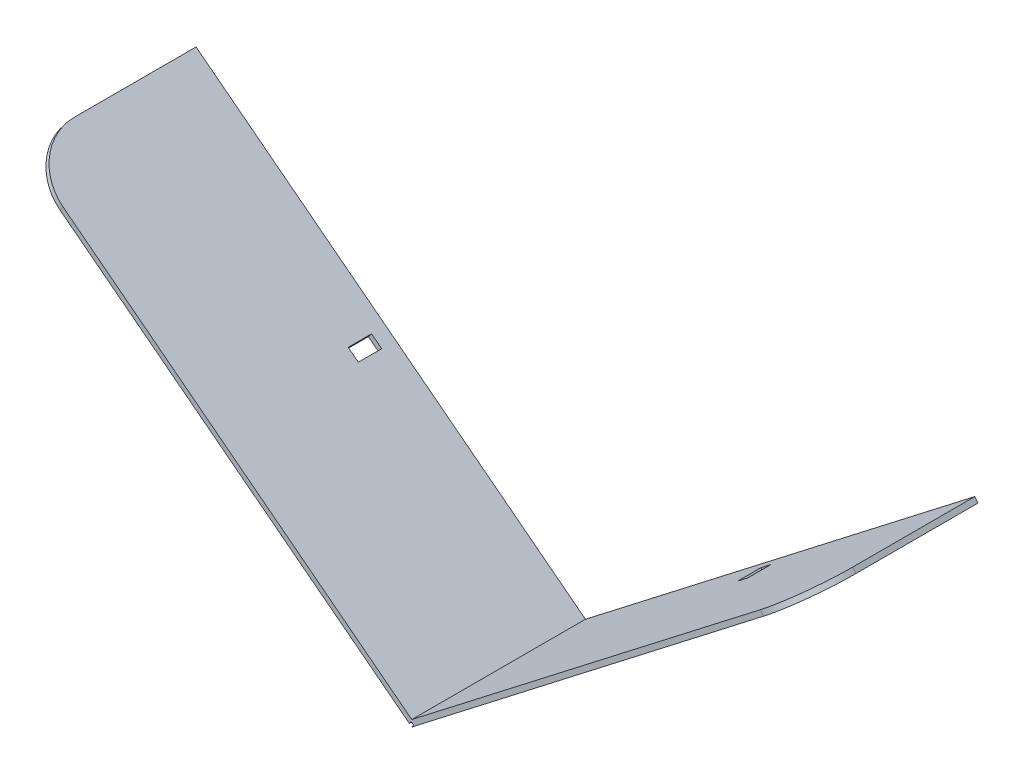
SolidWorks part; units mm, degrees
material "white foam"
ref_plane "Front Plane" through (0, 0, 0) normal (0, 0, 1) x (1, 0, 0)
ref_plane "Top Plane" through (0, 0, 0) normal (0, 1, 0) x (1, 0, 0)
ref_plane "Right Plane" through (0, 0, 0) normal (1, 0, 0) x (0, 0, -1)
sketch "Sketch1" plane through (0, 0, 0) normal (0, 0, 1) x (1, 0, 0)
  line L0 (0, 0) -> (380.0247, 293.7164)
  line L1 (0, 0) -> (-380.0247, 293.7164)
  line L2 (-380.0247, 0) -> (380.0247, 0) construction
  line L3 (0, 6.3193) -> (376.967, 297.6726)
  line L4 (0, 6.3193) -> (-376.967, 297.6726)
  line L5 (380.0247, 293.7164) -> (376.967, 297.6726)
  line L6 (-380.0247, 293.7164) -> (-376.967, 297.6726)
  point P7 (0, 0)
  dimension "D1" = 37.7
  dimension "D2" = 37.7
  dimension "D3" = 480.3
  dimension "D4" = 5
extrude "Boss-Extrude1" add sketch "Sketch1" against normal blind 240.2
sketch "Sketch2" plane through (0, 0, 0) normal (0, 1, 0) x (1, 0, 0)
  line L0 (-380.0247, 240.2) -> (-380.0247, 0) construction
  line L1 (380.0247, 240.2) -> (-380.0247, 240.2)
  line L2 (380.0247, 240.2) -> (380.0247, 168.14)
  line L3 (380.0247, 168.14) -> (-380.0247, 168.14)
  line L4 (-380.0247, 240.2) -> (-380.0247, 168.14)
  dimension "D1" = 72.06
extrude "Cut-Extrude3" cut sketch "Sketch2" along normal through all both and the other way through all contours L1 L4 L3 L2
sketch "Sketch3" plane through (3.0576, 3.9561, 0) normal (0.6115, 0.7912, 0) x (0.7912, -0.6115, 0)
  line L0 (-242.0822, 168.14) -> (-242.0822, 118.14) construction
  line L1 (-480.3, 168.14) -> (-3.8644, 168.14) construction
  line L3 (-248.2822, 131.84) -> (-235.8822, 131.84)
  line L4 (-248.2822, 131.84) -> (-248.2822, 154.44)
  line L5 (-248.2822, 154.44) -> (-235.8822, 154.44)
  line L6 (-235.8822, 131.84) -> (-235.8822, 154.44)
  line L7 (-248.2822, 131.84) -> (-235.8822, 154.44) construction
  line L8 (-248.2822, 154.44) -> (-235.8822, 131.84) construction
  point P4 (-242.0822, 143.14)
  dimension "D1" = 50
  dimension "D2" = 12.4
  dimension "D3" = 22.6
extrude "Cut-Extrude4" cut sketch "Sketch3" against normal through all both and the other way through all
mirror "Mirror1" about plane through (0, 0, 0) normal (1, 0, 0) of "Cut-Extrude4"
fillet "Fillet1" radius 50 2 edges at (-378.4958, 295.6945, 0) (378.4958, 295.6945, 0)
sketch "Sketch4" plane through (3.0576, 3.9561, 0) normal (0.6115, 0.7912, 0) x (0.7912, -0.6115, 0)
  line L0 (-96.8294, 49.07) -> (-110.8994, 35) construction
  line L1 (-86.2228, 38.4634) -> (-100.2928, 24.3934)
  line L2 (-107.436, 59.6766) -> (-121.506, 45.6066)
  line L3 (-123.0122, 123.14) -> (-201.1522, 45) construction
  line L4 (-105.3346, 105.4623) -> (-183.4746, 27.3223)
  line L5 (-140.6899, 140.8177) -> (-218.8299, 62.6777)
  line L6 (-361.1522, 123.14) -> (-283.0122, 45) construction
  line L7 (-343.4746, 140.8177) -> (-265.3346, 62.6777)
  line L8 (-378.8299, 105.4623) -> (-300.6899, 27.3223)
  line L9 (-387.335, 49.07) -> (-373.265, 35) construction
  line L10 (-376.7284, 59.6766) -> (-362.6584, 45.6066)
  line L11 (-397.9416, 38.4634) -> (-383.8716, 24.3934)
  line L12 (-3.8644, 0) -> (-430.3, 0) construction
  line L13 (-3.8644, 168.14) -> (-3.8644, 0) construction
  line L14 (-3.8644, 0) -> (-3.8644, 84.07) construction
  line L15 (-3.8644, 84.07) -> (-3.8644, 168.14) construction
  line L16 (-242.0822, 131.84) -> (-242.0822, 0) construction
  line L18 (-110.8994, 35) -> (-242.0822, 35) construction
  line L19 (-242.0822, 35) -> (-373.265, 35) construction
  line L20 (-435.3, 125.4623) -> (-435.3, 85.4623) construction
  line L21 (-420.3, 125.4623) -> (-420.3, 85.4623)
  line L22 (-450.3, 125.4623) -> (-450.3, 85.4623)
  line L23 (-480.3, 168.14) -> (-480.3, 50) construction
  line L25 (-248.2822, 131.84) -> (-235.8822, 131.84) construction
  line L26 (-3.8644, 0) -> (-430.3, 0) construction
  arc A0 (-86.2228, 38.4634) -> (-107.436, 59.6766) centre (-96.8294, 49.07) ccw
  arc A1 (-121.506, 45.6066) -> (-100.2928, 24.3934) centre (-110.8994, 35) ccw
  arc A2 (-105.3346, 105.4623) -> (-140.6899, 140.8177) centre (-123.0122, 123.14) ccw
  arc A3 (-218.8299, 62.6777) -> (-183.4746, 27.3223) centre (-201.1522, 45) ccw
  arc A4 (-343.4746, 140.8177) -> (-378.8299, 105.4623) centre (-361.1522, 123.14) ccw
  arc A5 (-300.6899, 27.3223) -> (-265.3346, 62.6777) centre (-283.0122, 45) ccw
  arc A6 (-376.7284, 59.6766) -> (-397.9416, 38.4634) centre (-387.335, 49.07) ccw
  arc A7 (-383.8716, 24.3934) -> (-362.6584, 45.6066) centre (-373.265, 35) ccw
  circle A8 centre (-242.0822, 105.4623) radius 15
  arc A9 (-420.3, 125.4623) -> (-450.3, 125.4623) centre (-435.3, 125.4623) ccw
  arc A10 (-450.3, 85.4623) -> (-420.3, 85.4623) centre (-435.3, 85.4623) ccw
  point P2 (-103.8644, 42.035)
  point P7 (-162.0822, 84.07)
  point P14 (-322.0822, 84.07)
  point P21 (-380.3, 42.035)
  point P34 (-3.8644, 84.07)
  point P40 (-3.8644, 42.035)
  point P44 (-435.3, 105.4623)
  point P59 (-242.0822, 131.84)
  dimension "D7" = 25
  dimension "D8" = 15
  dimension "D10" = 15
  dimension "D11" = 25
  dimension "D12" = 30
  dimension "D13" = 30
  dimension "D14" = 15
  dimension "D1" = 45
  dimension "D2" = 135
  dimension "D3" = 35
  dimension "D4" = 45
  dimension "D5" = 80
  dimension "D6" = 80
  dimension "D9" = 100
  dimension "D15" = 40
extrude "Cut-Extrude5" [suppressed] cut sketch "Sketch4" against normal through all both and the other way through all
mirror "Mirror2" [suppressed] about plane through (0, 0, 0) normal (1, 0, 0)
sketch "Sketch5" plane through (0, 0, 0) normal (-0.6115, -0.7912, 0) x (0.7912, -0.6115, 0)
  line L0 (0, -168.14) -> (-480.3, -168.14) construction
  line L1 (0, 0) -> (-3, 0)
  line L2 (0, 0) -> (0, -33.628)
  line L3 (0, -33.628) -> (-3, -33.628)
  line L4 (-3, 0) -> (-3, -33.628)
  line L5 (0, -33.628) -> (-3, -33.628)
  line L6 (0, -33.628) -> (0, -67.256)
  line L7 (0, -67.256) -> (-3, -67.256)
  line L8 (-3, -33.628) -> (-3, -67.256)
  line L9 (0, -67.256) -> (-3, -67.256)
  line L10 (0, -67.256) -> (0, -100.884)
  line L11 (0, -100.884) -> (-3, -100.884)
  line L12 (-3, -67.256) -> (-3, -100.884)
  line L13 (0, -100.884) -> (-3, -100.884)
  line L14 (0, -100.884) -> (0, -134.512)
  line L15 (0, -134.512) -> (-3, -134.512)
  line L16 (-3, -100.884) -> (-3, -134.512)
  line L17 (0, -134.512) -> (-3, -134.512)
  line L18 (0, -134.512) -> (0, -168.14)
  line L19 (0, -168.14) -> (-3, -168.14)
  line L20 (-3, -134.512) -> (-3, -168.14)
  line M46 (0, 0) -> (-430.3, 0)
  line M49 (-480.3, -168.14) -> (0, -168.14)
  line M50 (0, -168.14) -> (0, 0)
  dimension "D1" = 3
extrude "Cut-Extrude6" cut sketch "Sketch5" against normal blind 3 contours L4 L3 M46 M50 | L7 L12 L11 M50 | L15 L20 M49 M50
equation "\"D3@Sketch1\"=960.6/2"
equation "\"D1@Boss-Extrude1\"=240.2"
